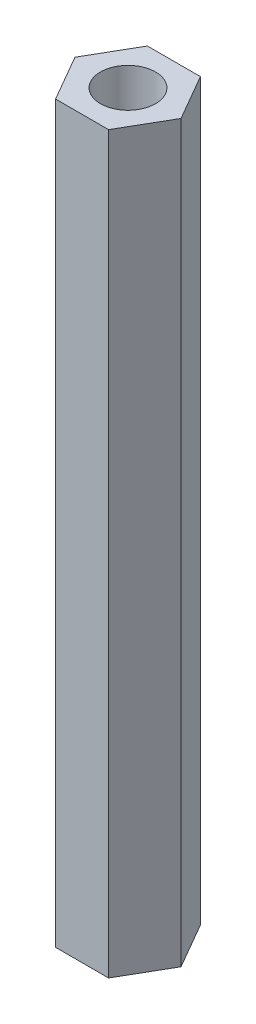
SolidWorks part; units mm, degrees
ref_plane "Front Plane" through (0, 0, 0) normal (0, 0, 1) x (1, 0, 0)
ref_plane "Top Plane" through (0, 0, 0) normal (0, 1, 0) x (1, 0, 0)
ref_plane "Right Plane" through (0, 0, 0) normal (1, 0, 0) x (0, 0, -1)
sketch "Sketch1" plane through (0, 0, 0) normal (0, 1, 0) x (1, 0, 0)
  line L1 (2.8868, 0) -> (1.4434, 2.5)
  line L2 (1.4434, 2.5) -> (-1.4434, 2.5)
  line L3 (-1.4434, 2.5) -> (-2.8868, 0)
  line L4 (-2.8868, 0) -> (-1.4434, -2.5)
  line L5 (-1.4434, -2.5) -> (1.4434, -2.5)
  line L6 (1.4434, -2.5) -> (2.8868, 0)
  circle A0 centre (0, 0) radius 2.5 construction
  dimension "D1" = 5
extrude "Boss-Extrude1" add sketch "Sketch1" along normal mid plane 40
sketch "Sketch2" plane through (0, 20, 0) normal (0, 1, 0) x (1, 0, 0)
  circle A0 centre (0, 0) radius 1.5
  dimension "D1" = 3
extrude "Cut-Extrude1" cut sketch "Sketch2" against normal blind 6
mirror "Mirror1" about plane through (0, 0, 0) normal (1, 0, 0) of "Cut-Extrude1" second plane through (0, 0, 0) second plane normal (0, 1, 0)
